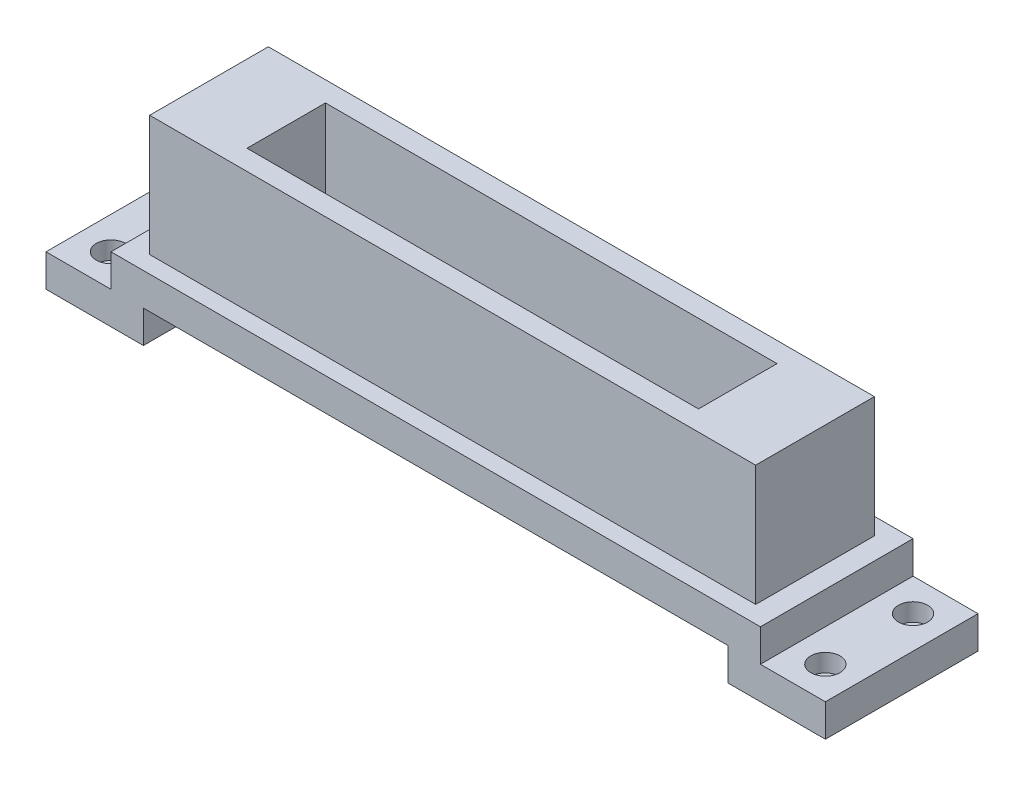
SolidWorks part; units mm, degrees
ref_plane "前视基准面" through (0, 0, 0) normal (0, 0, 1) x (1, 0, 0)
ref_plane "上视基准面" through (0, 0, 0) normal (0, 1, 0) x (1, 0, 0)
ref_plane "右视基准面" through (0, 0, 0) normal (1, 0, 0) x (0, 0, -1)
other "Configuration Table"
ref_plane "基准面1" through (0, -20, 0) normal (0, -1, 0) x (1, 0, 0)
sketch "草图1" plane through (0, -20, 0) normal (0, -1, 0) x (1, 0, 0)
  line L0 (240, 47) -> (-240, 47)
  line L1 (-240, 47) -> (-240, -47)
  line L2 (-240, -47) -> (240, -47)
  line L3 (240, -47) -> (240, 47)
extrude "凸台-拉伸1" add sketch "草图1" against normal blind 40
sketch "草图2" plane through (0, 0, -47) normal (0, 0, -1) x (-1, 0, 0)
  line L0 (200, 20) -> (200, 0)
  line L1 (200, 0) -> (240, 0)
  line L2 (240, 0) -> (240, 20)
  line L3 (240, 20) -> (200, 20)
extrude "切除-拉伸1" cut sketch "草图2" against normal through all
sketch "草图3" plane through (0, 0, -47) normal (0, 0, -1) x (-1, 0, 0)
  line L0 (-180, -20) -> (180, -20)
  line L1 (180, -20) -> (180, 0)
  line L2 (180, 0) -> (-180, 0)
  line L3 (-180, 0) -> (-180, -20)
extrude "切除-拉伸2" cut sketch "草图3" against normal through all
sketch "草图4" plane through (0, 0, -47) normal (0, 0, -1) x (-1, 0, 0)
  line L0 (-240, 0) -> (-200, 0)
  line L1 (-200, 0) -> (-200, 20)
  line L2 (-200, 20) -> (-240, 20)
  line L3 (-240, 20) -> (-240, 0)
extrude "切除-拉伸3" cut sketch "草图4" against normal through all
hole_wizard "M10 六角头螺栓的柱形沉头孔1" positions "草图8" profile "草图7" counterbore size "M10" standard "ANSI Metric"
sketch "草图8" plane through (0, 0, 0) normal (0, 1, 0) x (1, 0, 0)
  point P0 (220, -27)
  point P1 (220, 27)
  point P2 (-220, -27)
  point P3 (-220, 27)
sketch "草图7" plane through (220, 0, 27) normal (1, 0, 0) x (0, 0, 1)
  line L0 (0, 0) -> (0, 20)
  line L1 (0, 20) -> (5.5, 20)
  line L3 (5.5, 20) -> (5.5, 11)
  line L4 (5.5, 11) -> (9, 11)
  line L5 (9, 11) -> (9, 0)
  line L7 (9, 0) -> (0, 0)
  line L11 (0, -6.35) -> (0, 107.95) construction
  dimension "通孔孔直径" = 11
  dimension "通孔孔深度" = 20
  dimension "柱形沉头孔直径" = 18
  dimension "柱形沉头孔深度" = 11
ref_plane "基准面2" through (-200, 0, 0) normal (-1, 0, 0) x (0, 0, 1)
sketch "草图14" plane through (0, 20, 0) normal (0, 1, 0) x (1, 0, 0)
  line L1 (-186.6148, -36.5494) -> (186.6148, -36.5494)
  line L2 (-186.6148, -36.5494) -> (-186.6148, 36.5494)
  line L3 (-186.6148, 36.5494) -> (186.6148, 36.5494)
  line L4 (186.6148, -36.5494) -> (186.6148, 36.5494)
  line L5 (-186.6148, -36.5494) -> (186.6148, 36.5494) construction
  line L6 (-186.6148, 36.5494) -> (186.6148, -36.5494) construction
  point P0 (0, 0)
extrude "凸台-拉伸2" add sketch "草图14" along normal blind 74.29
sketch "草图15" plane through (0, 94.29, 0) normal (0, 1, 0) x (1, 0, 0)
  line L1 (-139.0426, -24.1729) -> (139.0426, -24.1729)
  line L2 (-139.0426, -24.1729) -> (-139.0426, 24.1729)
  line L3 (-139.0426, 24.1729) -> (139.0426, 24.1729)
  line L4 (139.0426, -24.1729) -> (139.0426, 24.1729)
  line L5 (-139.0426, -24.1729) -> (139.0426, 24.1729) construction
  line L6 (-139.0426, 24.1729) -> (139.0426, -24.1729) construction
  point P0 (0, 0)
extrude "切除-拉伸4" cut sketch "草图15" against normal up to surface (74.29 mm away) up to face at (0, 20, 0)
ref_plane "基准面3" through (186.6148, 94.29, -36.5494) normal (-1, 0, 0) x (0, 0, 1)
